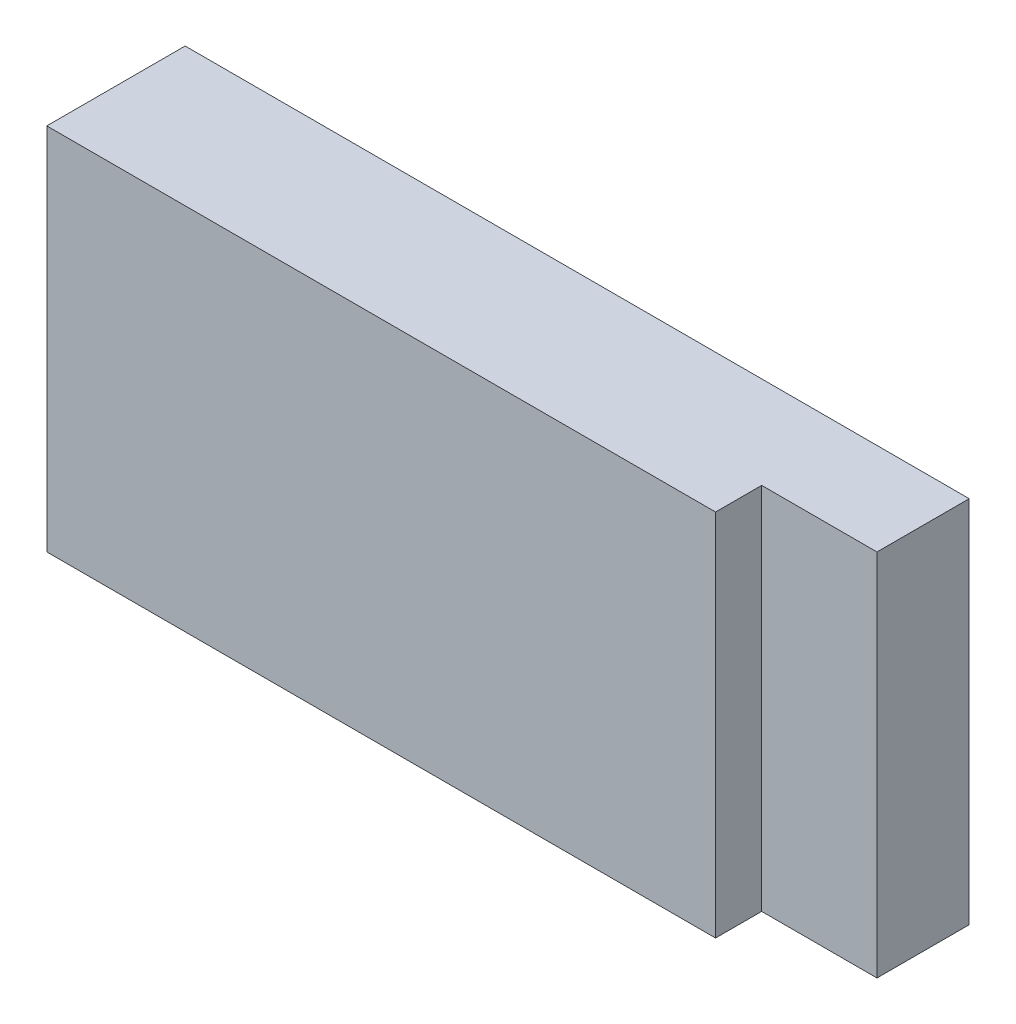
SolidWorks part; units mm, degrees
material "ПК/АБС"
ref_plane "Спереди" through (0, 0, 0) normal (0, 0, 1) x (1, 0, 0)
ref_plane "Сверху" through (0, 0, 0) normal (0, 1, 0) x (1, 0, 0)
ref_plane "Справа" through (0, 0, 0) normal (1, 0, 0) x (0, 0, -1)
sketch "Эскиз1" plane through (0, 0, 0) normal (0, 0, 1) x (1, 0, 0)
  line L0 (-13.9364, 7.3887) -> (20.0636, 7.3887)
  line L1 (20.0636, 7.3887) -> (20.0636, -8.6113)
  line L2 (20.0636, -8.6113) -> (-13.9364, -8.6113)
  line L3 (-13.9364, -8.6113) -> (-13.9364, 7.3887)
  dimension "D1" = 34
  dimension "D2" = 16
extrude "Бобышка-Вытянуть1" add sketch "Эскиз1" along normal blind 4
sketch "Эскиз2" plane through (0, 0, 4) normal (0, 0, 1) x (1, 0, 0)
  line L0 (15.0636, 7.3887) -> (15.0636, -8.6113)
  line L1 (20.0636, 7.3887) -> (-13.9364, 7.3887) construction
  line L2 (-13.9364, -8.6113) -> (20.0636, -8.6113) construction
  line L3 (-13.9364, 7.3887) -> (-13.9364, -8.6113) construction
  line L8 (-13.9364, 7.3887) -> (-13.9364, -8.6113)
  line L9 (-13.9364, -8.6113) -> (20.0636, -8.6113)
  line L10 (20.0636, -8.6113) -> (20.0636, 7.3887)
  line L11 (20.0636, 7.3887) -> (-13.9364, 7.3887)
  line L12 (-13.9364, 7.3887) -> (-13.9364, -8.6113)
  line L13 (-13.9364, -8.6113) -> (15.0636, -8.6113)
  line L15 (15.0636, 7.3887) -> (-13.9364, 7.3887)
  dimension "D1" = 29
  dimension "D2" = 0
extrude "Бобышка-Вытянуть2" add sketch "Эскиз2" along normal blind 2
